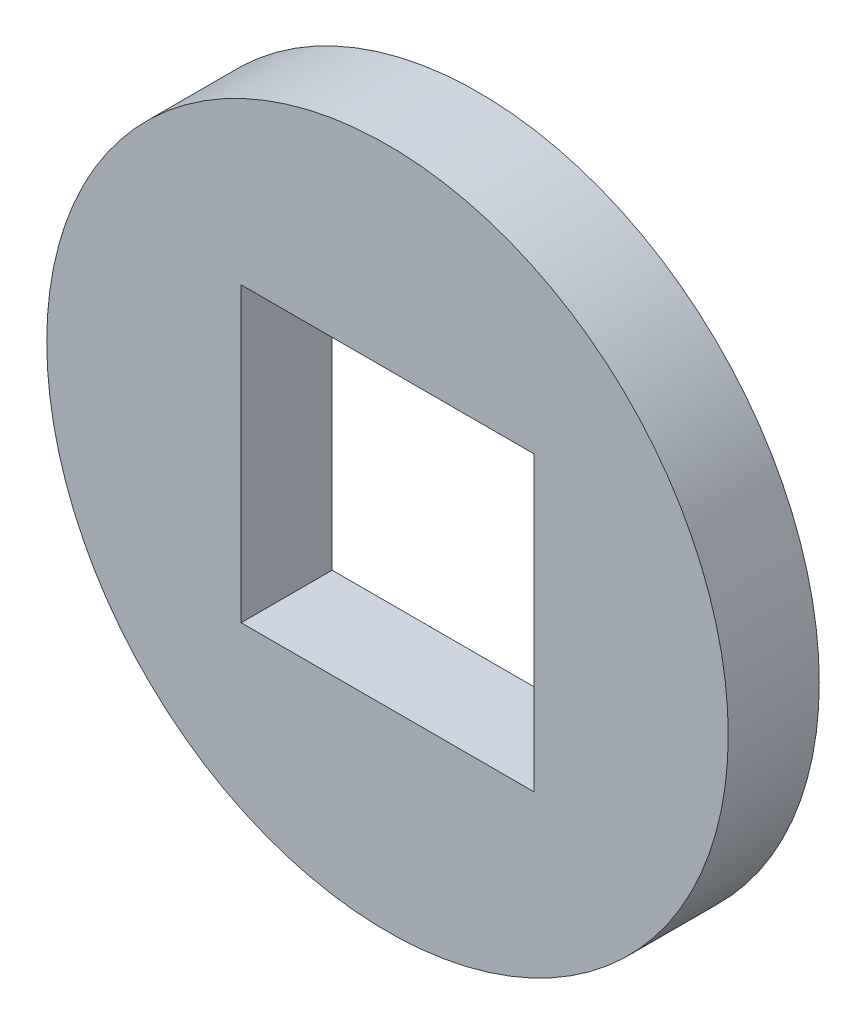
SolidWorks part; units mm, degrees
ref_plane "Front Plane" through (0, 0, 0) normal (0, 0, 1) x (1, 0, 0)
ref_plane "Top Plane" through (0, 0, 0) normal (0, 1, 0) x (1, 0, 0)
ref_plane "Right Plane" through (0, 0, 0) normal (1, 0, 0) x (0, 0, -1)
sketch "Sketch1" plane through (0, 0, 0) normal (0, 0, 1) x (1, 0, 0)
  line L1 (-4.6355, 4.6355) -> (4.6355, 4.6355)
  line L2 (-4.6355, 4.6355) -> (-4.6355, -4.6355)
  line L3 (-4.6355, -4.6355) -> (4.6355, -4.6355)
  line L4 (4.6355, 4.6355) -> (4.6355, -4.6355)
  line L5 (-4.6355, 4.6355) -> (4.6355, -4.6355) construction
  line L6 (-4.6355, -4.6355) -> (4.6355, 4.6355) construction
  circle A0 centre (0, 0) radius 10.795
  dimension "D3" = 21.59
  dimension "D1" = 9.271
  dimension "D2" = 9.271
extrude "Boss-Extrude1" add sketch "Sketch1" along normal blind 2.8829
